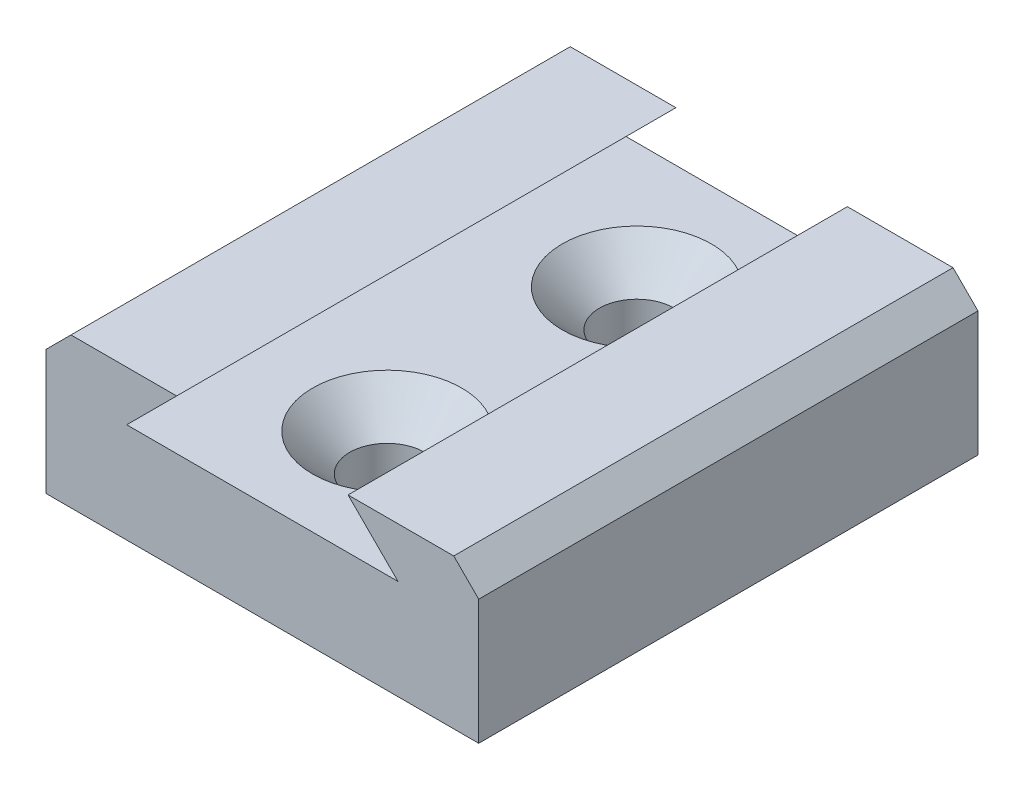
SolidWorks part; units mm, degrees
ref_plane "Front Plane" through (0, 0, 0) normal (0, 0, 1) x (1, 0, 0)
ref_plane "Top Plane" through (0, 0, 0) normal (0, 1, 0) x (1, 0, 0)
ref_plane "Right Plane" through (0, 0, 0) normal (1, 0, 0) x (0, 0, -1)
sketch "Sketch2" plane through (0, 0, 0) normal (0, 0, 1) x (1, 0, 0)
  line L0 (-13, 0) -> (13, 0)
  line L1 (13, 0) -> (13, 7.5)
  line L2 (13, 7.5) -> (11.5, 9)
  line L3 (11.5, 9) -> (5.15, 9)
  line L4 (5.15, 9) -> (8.15, 6)
  line L5 (8.15, 6) -> (-8.15, 6)
  line L6 (-8.15, 6) -> (-5.15, 9)
  line L7 (-5.15, 9) -> (-11.5, 9)
  line L8 (-11.5, 9) -> (-13, 7.5)
  line L9 (-13, 7.5) -> (-13, 0)
  point P0 (0, 0)
  point P12 (0, 6)
  dimension "D1" = 16.3
  dimension "D2" = 45
  dimension "D3" = 3
  dimension "D4" = 45
  dimension "D5" = 26
  dimension "D6" = 1.5
  dimension "D7" = 1.5
  dimension "D8" = 6
extrude "Boss-Extrude1" add sketch "Sketch2" along normal blind 30
sketch "Sketch7" plane through (0, 6, 0) normal (0, 1, 0) x (1, 0, 0)
  line L6 (0, 0) -> (0, -15) construction
  line L7 (0, -15) -> (0, -30) construction
  line L8 (8.15, -30) -> (-8.15, -30) construction
  point P21 (0, -7.5)
  point P23 (0, -22.5)
hole_wizard "CSK for M4 Hex Socket Countersunk Cap Screw1" positions "Sketch7" profile "Sketch8" countersink size "M4" standard "ISO" end condition up to next
sketch "Sketch8" plane through (0, 6, 22.5) normal (1, 0, 0) x (0, 0, 1)
  line L0 (0, 0) -> (0, 6)
  line L1 (0, 6) -> (2.25, 6)
  line L2 (2.25, 6) -> (2.25, 2.23)
  line L3 (2.25, 2.23) -> (4.48, 0)
  line L5 (4.48, 0) -> (0, 0)
  line L6 (-2.25, 2.23) -> (-4.48, 0) construction
  line L11 (0, -6.35) -> (0, 107.95) construction
  dimension "Thru Hole Dia." = 4.5
  dimension "Thru Hole Depth" = 6
  dimension "Near C'Sink Dia." = 8.96
  dimension "Near C'Sink Angle" = 90
